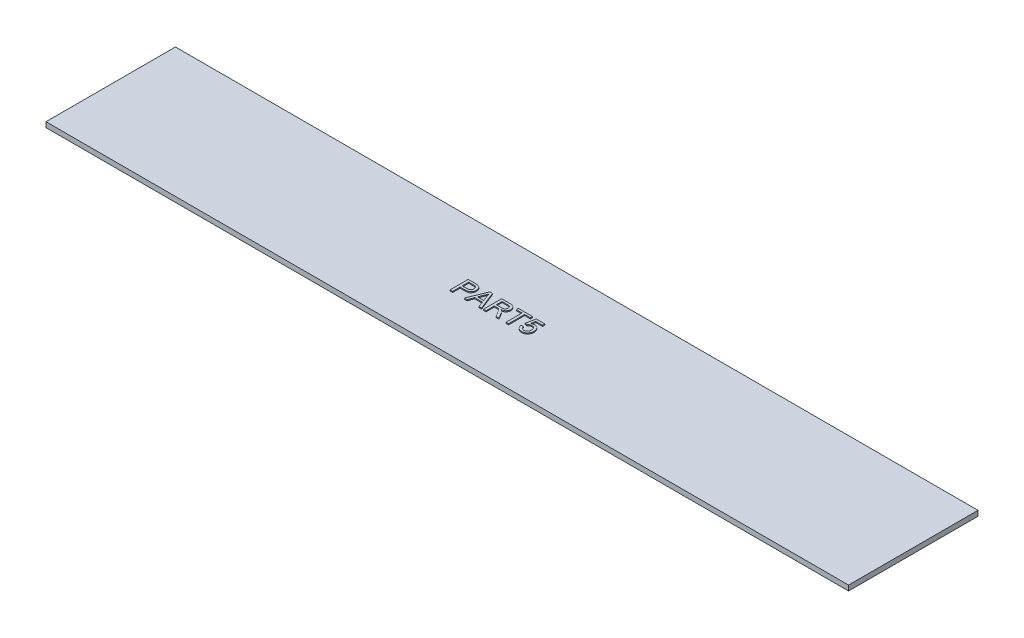
SolidWorks part; units mm, degrees
ref_plane "前视基准面" through (0, 0, 0) normal (0, 0, 1) x (1, 0, 0)
ref_plane "上视基准面" through (0, 0, 0) normal (0, 1, 0) x (1, 0, 0)
ref_plane "右视基准面" through (0, 0, 0) normal (1, 0, 0) x (0, 0, -1)
other "Configuration Table"
sketch "草图1" plane through (0, 0, 0) normal (0, 1, 0) x (1, 0, 0)
  line L1 (0, 0) -> (155, 0)
  line L2 (0, 0) -> (0, 25)
  line L3 (0, 25) -> (155, 25)
  line L4 (155, 0) -> (155, 25)
  dimension "D1" = 25
  dimension "D2" = 155
extrude "凸台-拉伸1" add sketch "草图1" along normal blind 1
sketch "草图2" plane through (0, 1, 0) normal (0, 1, 0) x (1, 0, 0)
  line L0 (32.4435, 10.6934) -> (117.1047, 10.6934) construction
  text T0 "PART5" font "Arial" height 3.5
extrude "凸台-拉伸2" add sketch "草图2" along normal blind 0.2
